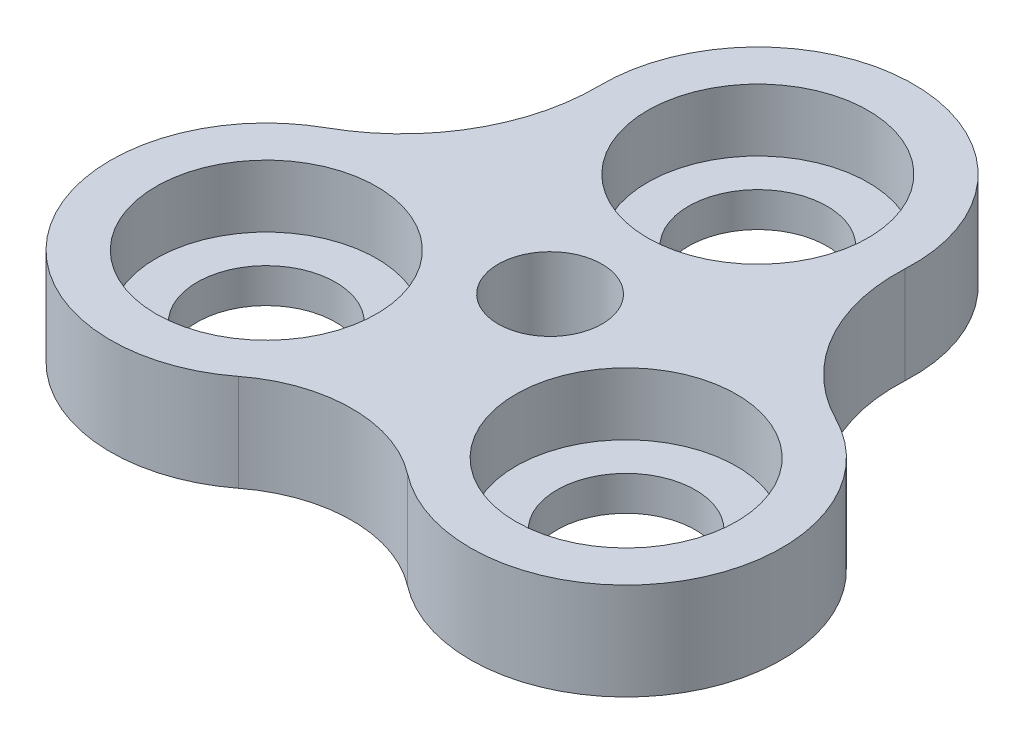
SolidWorks part; units mm, degrees
ref_plane "Front Plane" through (0, 0, 0) normal (0, 0, 1) x (1, 0, 0)
ref_plane "Top Plane" through (0, 0, 0) normal (0, 1, 0) x (1, 0, 0)
ref_plane "Right Plane" through (0, 0, 0) normal (1, 0, 0) x (0, 0, -1)
sketch "Sketch1" plane through (0, 0, 0) normal (0, 1, 0) x (1, 0, 0)
  circle A0 centre (0, 0) radius 3
  circle A1 centre (0, 12) radius 6.375
  arc A2 (8.9876, 11.5283) -> (-8.999, 11.8661) centre (0, 12) ccw
  circle A3 centre (10.3923, -6) radius 6.375
  arc A4 (4.8833, -13.117) -> (14.4776, 2.0194) centre (10.3923, -6) ccw
  circle A5 centre (-10.3923, -6) radius 6.375
  arc A6 (-14.7759, 1.8603) -> (-4.8833, -13.117) centre (-10.3923, -6) ccw
  arc A7 (-14.7759, 1.8603) -> (-8.999, 11.8661) centre (-20.2626, 11.6986) ccw
  arc A8 (8.9876, 11.5283) -> (14.4776, 2.0194) centre (19.0525, 11) ccw
  arc A9 (-4.8833, -13.117) -> (4.8833, -13.117) centre (0, -19.4257) cw
  point P15 (0, 0)
  dimension "D1" = 6
  dimension "D2" = 12.75
  dimension "D3" = 18
  dimension "D5" = 12
  dimension "D4" = 3
extrude "Boss-Extrude1" add sketch "Sketch1" along normal blind 5.6 contours A5 | A3 | A1 | A6 A9 A4 A8 A2 A7 A0 A1 A3 A5
sketch "Sketch2" plane through (0, 5.6, 0) normal (0, 1, 0) x (1, 0, 0)
  circle A0 centre (-10.3923, -6) radius 6.375
  circle A1 centre (0, 12) radius 6.375
  circle A2 centre (10.3923, -6) radius 6.375
  dimension "D1" = 12.75
extrude "Cut-Extrude1" cut sketch "Sketch2" against normal blind 3.6
sketch "Sketch3" plane through (0, 2, 0) normal (0, 1, 0) x (1, 0, 0)
  circle A0 centre (-10.3923, -6) radius 4
  circle A1 centre (0, 12) radius 4
  circle A2 centre (10.3923, -6) radius 4
  dimension "D1" = 8
extrude "Cut-Extrude2" cut sketch "Sketch3" against normal through all
